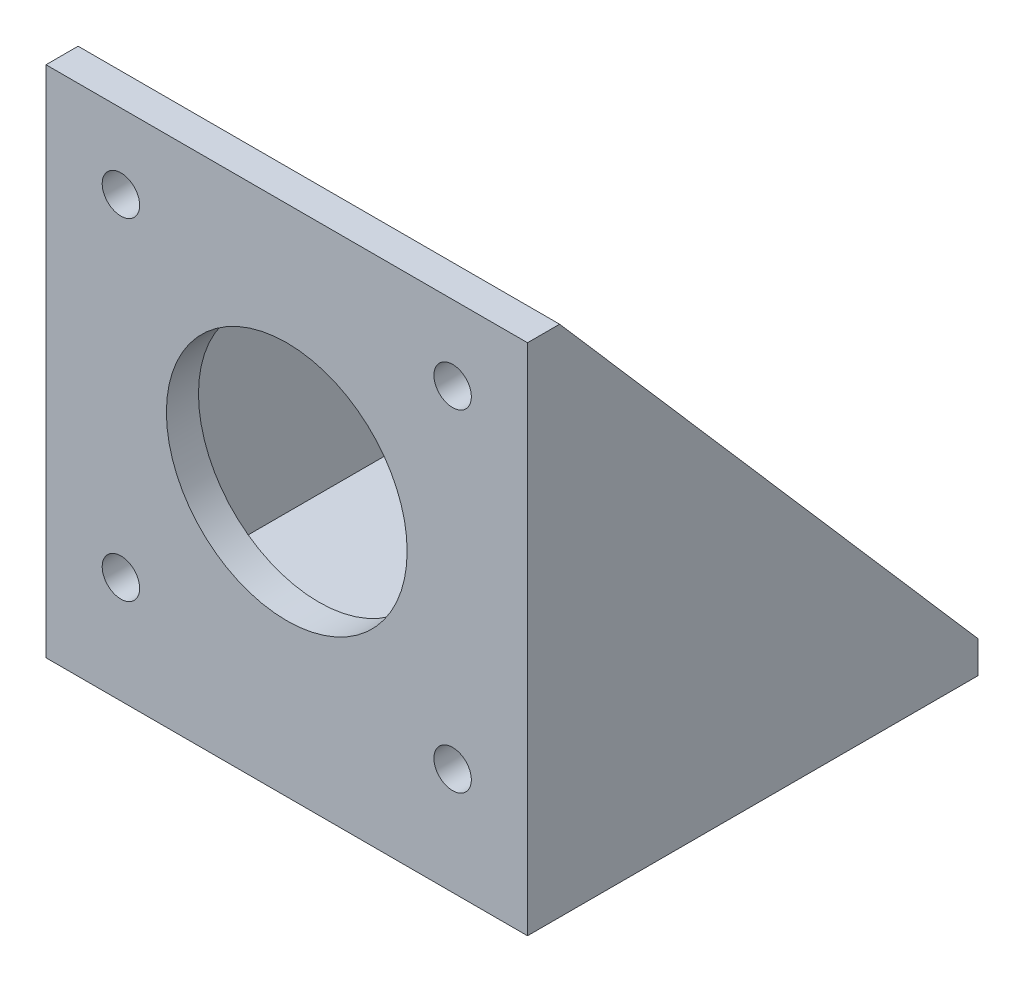
SolidWorks part; units mm, degrees
ref_plane "Front Plane" through (0, 0, 0) normal (0, 0, 1) x (1, 0, 0)
ref_plane "Top Plane" through (0, 0, 0) normal (0, 1, 0) x (1, 0, 0)
ref_plane "Right Plane" through (0, 0, 0) normal (1, 0, 0) x (0, 0, -1)
sketch "Sketch1" plane through (0, 0, 0) normal (0, 1, 0) x (1, 0, 0)
  line L1 (-22.5, -21.05) -> (22.5, -21.05)
  line L2 (-22.5, -21.05) -> (-22.5, 21.05)
  line L3 (-22.5, 21.05) -> (22.5, 21.05)
  line L4 (22.5, -21.05) -> (22.5, 21.05)
  line L5 (-22.5, -21.05) -> (22.5, 21.05) construction
  line L6 (-22.5, 21.05) -> (22.5, -21.05) construction
  point P0 (0, 0)
  dimension "D1" = 45
  dimension "D2" = 42.1
extrude "Boss-Extrude1" add sketch "Sketch1" along normal blind 3
sketch "Sketch2" plane through (0, 3, 0) normal (0, -1, 0) x (1, 0, 0)
  line L0 (22.5, 21.05) -> (22.5, -21.05) construction
  line L1 (-22.5, 21.05) -> (22.5, 21.05)
  line L2 (-22.5, 21.05) -> (-22.5, 18.05)
  line L3 (-22.5, 18.05) -> (22.5, 18.05)
  line L4 (22.5, 21.05) -> (22.5, 18.05)
  dimension "D1" = 3
extrude "Boss-Extrude2" add sketch "Sketch2" against normal blind 45
sketch "Sketch4" plane through (0, 0, 18.05) normal (0, 0, -1) x (-1, 0, 0)
  line L0 (-998.7982, 25.5) -> (49001.2018, 25.5) construction
  line L1 (0, -1000) -> (0, 49000) construction
  line L2 (22.5, 48) -> (-22.5, 48) construction
  circle A0 centre (0, 25.5) radius 11.25
  dimension "D2" = 22.5
  dimension "D1" = 22.5
extrude "Cut-Extrude1" cut sketch "Sketch4" against normal through all
sketch "Sketch5" plane through (0, 0, 18.05) normal (0, 0, -1) x (-1, 0, 0)
  line L1 (-15.5, 10) -> (15.5, 10) construction
  line L2 (-15.5, 10) -> (-15.5, 41) construction
  line L3 (-15.5, 41) -> (15.5, 41) construction
  line L4 (15.5, 10) -> (15.5, 41) construction
  line L5 (-15.5, 10) -> (15.5, 41) construction
  line L6 (-15.5, 41) -> (15.5, 10) construction
  circle A0 centre (-15.5, 41) radius 1.75
  circle A1 centre (15.5, 41) radius 1.75
  circle A2 centre (15.5, 10) radius 1.75
  circle A3 centre (-15.5, 10) radius 1.75
  point P0 (0, 25.5)
  dimension "D3" = 3.5
  dimension "D4" = 3.5
  dimension "D5" = 3.5
  dimension "D6" = 3.5
  dimension "D1" = 31
  dimension "D2" = 31
extrude "Cut-Extrude2" cut sketch "Sketch5" against normal through all
sketch "Sketch6" plane through (0, 3, 0) normal (0, 1, 0) x (1, 0, 0)
  line L0 (22.5, 21.05) -> (-22.5, 21.05) construction
  line L1 (12.5, 10) -> (-12.5, 10) construction
  line L2 (12.5, 10) -> (12.5, -10) construction
  line L3 (12.5, -10) -> (-12.5, -10) construction
  line L4 (-12.5, 10) -> (-12.5, -10) construction
  line L5 (12.5, 10) -> (-12.5, -10) construction
  line L6 (12.5, -10) -> (-12.5, 10) construction
  line L7 (-22.5, 21.05) -> (-22.5, -18.05) construction
  circle A0 centre (12.5, -10) radius 1.55
  circle A1 centre (-12.5, -10) radius 1.55
  circle A2 centre (-12.5, 10) radius 1.55
  circle A3 centre (12.5, 10) radius 1.55
  point P0 (0, 0)
  dimension "D5" = 3.1
  dimension "D6" = 3.1
  dimension "D7" = 3.1
  dimension "D8" = 3.1
  dimension "D1" = 20
  dimension "D2" = 25
  dimension "D3" = 11.05
  dimension "D4" = 10
extrude "Cut-Extrude3" cut sketch "Sketch6" against normal blind 3
sketch "Sketch8" plane through (22.5, 0, 0) normal (1, 0, 0) x (0, 0, -1)
  line L0 (-18.05, 48) -> (21.05, 3)
  line L1 (21.05, 3) -> (-18.05, 3)
  line L2 (-18.05, 3) -> (-18.05, 48)
extrude "Boss-Extrude3" add sketch "Sketch8" against normal blind 2.5
mirror "Mirror1" about plane through (0, 0, 0) normal (1, 0, 0) of "Boss-Extrude3"
